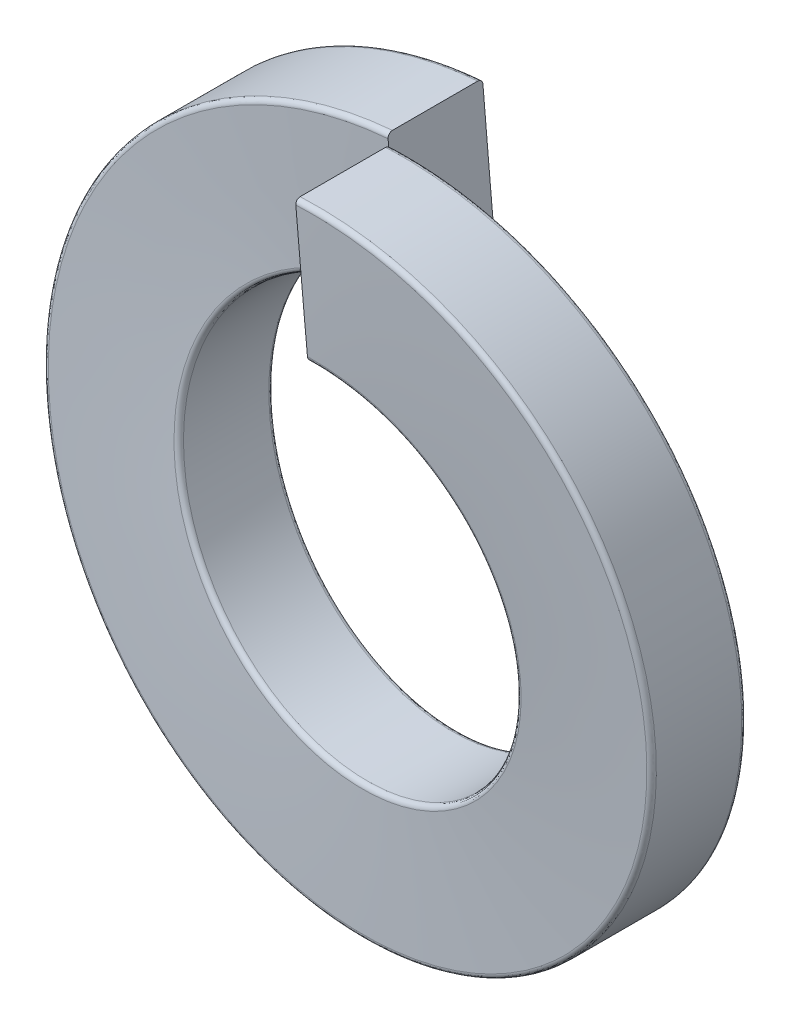
SolidWorks part; units mm, degrees
ref_plane "Front Plane" through (0, 0, 0) normal (0, 0, 1) x (1, 0, 0)
ref_plane "Top Plane" through (0, 0, 0) normal (0, 1, 0) x (1, 0, 0)
ref_plane "Right Plane" through (0, 0, 0) normal (1, 0, 0) x (0, 0, -1)
sketch "Sketch1" plane through (0, 0, 0) normal (0, 0, 1) x (1, 0, 0)
  circle A0 centre (0, 0) radius 6.5024
  circle A1 centre (0, 0) radius 11.0363
  dimension "OD" = 22.0726
  dimension "ID" = 13.0048
sketch "Sketch2" plane through (0, 0, 0) normal (1, 0, 0) x (0, 0, -1)
  line L0 (0, 0) -> (0, 11.0363) construction
  line L1 (0, 11.0363) -> (0, -11.0363) construction
  line L4 (0.3175, 11.0363) -> (3.4925, 11.0363)
  line L5 (3.4925, 11.0363) -> (3.4925, 6.5024)
  line L6 (3.4925, 6.5024) -> (0.3175, 6.5024)
  line L7 (0.3175, 6.5024) -> (0.3175, 11.0363)
  point P6 (0, 6.5024)
  point P14 (0, -11.0363)
  dimension "Thickness" = 3.175
  dimension "D1" = 0.3175
ref_plane "Plane1" through (0, 0, -3.4925) normal (0, 0, 1) x (1, 0, 0)
sketch "Sketch3" plane through (0, 0, -3.4925) normal (0, 0, 1) x (1, 0, 0)
  circle A0 centre (0, 0) radius 11.0363 construction
  circle A1 centre (0, 0) radius 11.0363
curve "Helix/Spiral1" pitch 3.4925 height 3.4925 turns 1
sketch "Sketch4" plane through (0, 0, 0) normal (1, 0, 0) x (0, 0, -1)
  line L0 (0.3175, 6.5024) -> (0.3175, 11.0363) construction
  line L1 (3.4925, 6.5024) -> (0.3175, 6.5024) construction
  line L2 (3.4925, 11.0363) -> (3.4925, 6.5024) construction
  line L3 (0.3175, 11.0363) -> (3.4925, 11.0363) construction
  line L4 (0.3175, 6.5024) -> (0.3175, 11.0363)
  line L5 (3.4925, 6.5024) -> (0.3175, 6.5024)
  line L6 (3.4925, 11.0363) -> (3.4925, 6.5024)
  line L7 (0.3175, 11.0363) -> (3.4925, 11.0363)
sweep "Sweep1" add profiles "Sketch4" path "Helix/Spiral1"
fillet "Fillet1" radius 0.1588 4 edges
sketch "Sketch5" plane through (0, 0, 0) normal (0, 0, 1) x (1, 0, 0)
  line L2 (0, 0) -> (-0.1926, 11.0346) construction
  line L3 (0, 11.0363) -> (0.3867, 6.4909)
  line L4 (-0.3852, 11.0296) -> (0, 6.5024)
  line L5 (-0.3852, 11.0296) -> (0, 0) construction
  line L6 (0, 0) -> (0, 11.0363) construction
  line L7 (0, 6.5024) -> (0, 0)
  line L8 (0, 0) -> (0.3867, 0)
  line L9 (0.3867, 0) -> (0.3867, 6.4909)
  circle A0 centre (0, 0) radius 11.0363 construction
  arc A1 (-0.3852, 11.0296) -> (0, 11.0363) centre (0, 0) cw
  circle A2 centre (0, 0) radius 6.5024 construction
  dimension "D1" = 2
extrude "Cut-Extrude1" cut sketch "Sketch5" against normal through all both and the other way through all
ref_plane "Contact Plane1" through (0, 0, 3.1743) normal (0, 0, 1) x (1, 0, 0)
ref_plane "Contact Plane2" through (0, 0, -3.4914) normal (0, 0, 1) x (1, 0, 0)
equation "\"D1@Sketch2\" = \"Thickness@Sketch2\" * 0.1"
equation "\"D4@Helix/Spiral1\" = \"Thickness@Sketch2\" + \"D1@Sketch2\""
equation "\"D1@Fillet1\"=\"D1@Sketch2\"*0.5"
